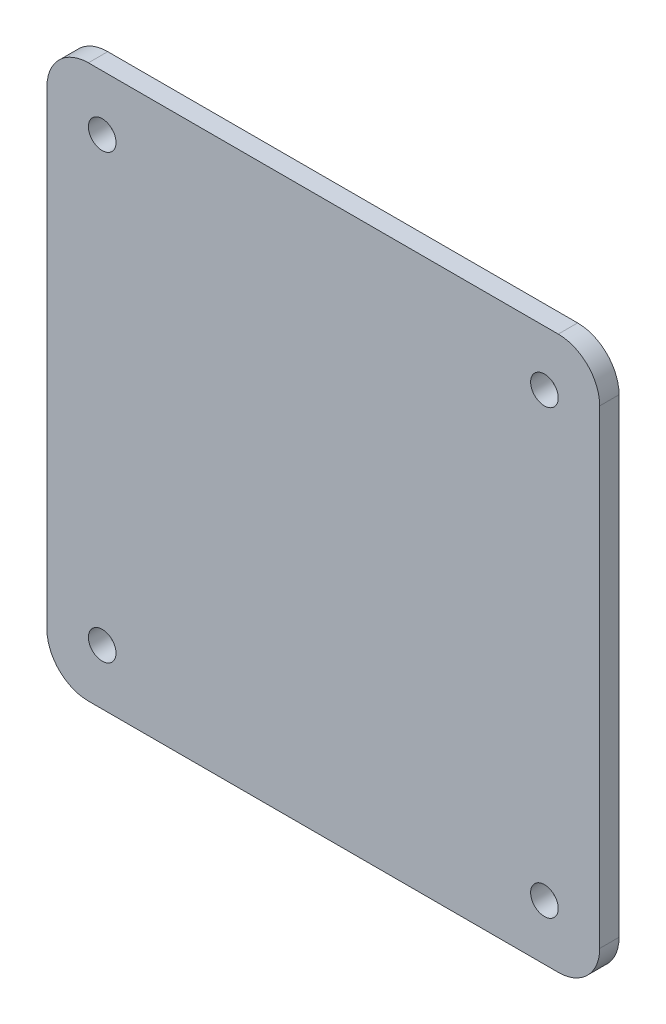
SolidWorks part; units mm, degrees
ref_plane "Plan de face" through (0, 0, 0) normal (0, 0, 1) x (1, 0, 0)
ref_plane "Plan de dessus" through (0, 0, 0) normal (0, 1, 0) x (1, 0, 0)
ref_plane "Plan de droite" through (0, 0, 0) normal (1, 0, 0) x (0, 0, -1)
sketch "Esquisse3" plane through (0, 0, 0) normal (0, 0, 1) x (1, 0, 0)
  line L1 (-100, -100) -> (100, -100)
  line L2 (-100, -100) -> (-100, 100)
  line L3 (-100, 100) -> (100, 100)
  line L4 (100, -100) -> (100, 100)
  line L5 (-80, -80) -> (80, -80) construction
  line L6 (-80, -80) -> (-80, 80) construction
  line L7 (-80, 80) -> (80, 80) construction
  line L8 (80, -80) -> (80, 80) construction
  circle A0 centre (80, 80) radius 5
  circle A1 centre (80, -80) radius 5
  circle A2 centre (-80, -80) radius 5
  circle A3 centre (-80, 80) radius 5
  point P4 (0, 0)
  dimension "D9" = 10
  dimension "D10" = 10
  dimension "D11" = 10
  dimension "D12" = 10
  dimension "D1" = 200
  dimension "D2" = 200
  dimension "D3" = 100
  dimension "D4" = 100
  dimension "D5" = 20
  dimension "D6" = 20
  dimension "D7" = 20
  dimension "D8" = 20
extrude "Boss.-Extru.2" add sketch "Esquisse3" along normal blind 7
fillet "Congé1" radius 15 4 edges at (-100, -100, 3.5) (-100, 100, 3.5) (100, 100, 3.5) (100, -100, 3.5)
sketch "Esquisse4" plane through (0, 0, 0) normal (0, 0, -1) x (-1, 0, 0)
  line L0 (0, -2.0063) -> (0, 1.8794) construction
  line L1 (-1.5319, 0) -> (1.4801, 0) construction
  point P5 (0, 0)
